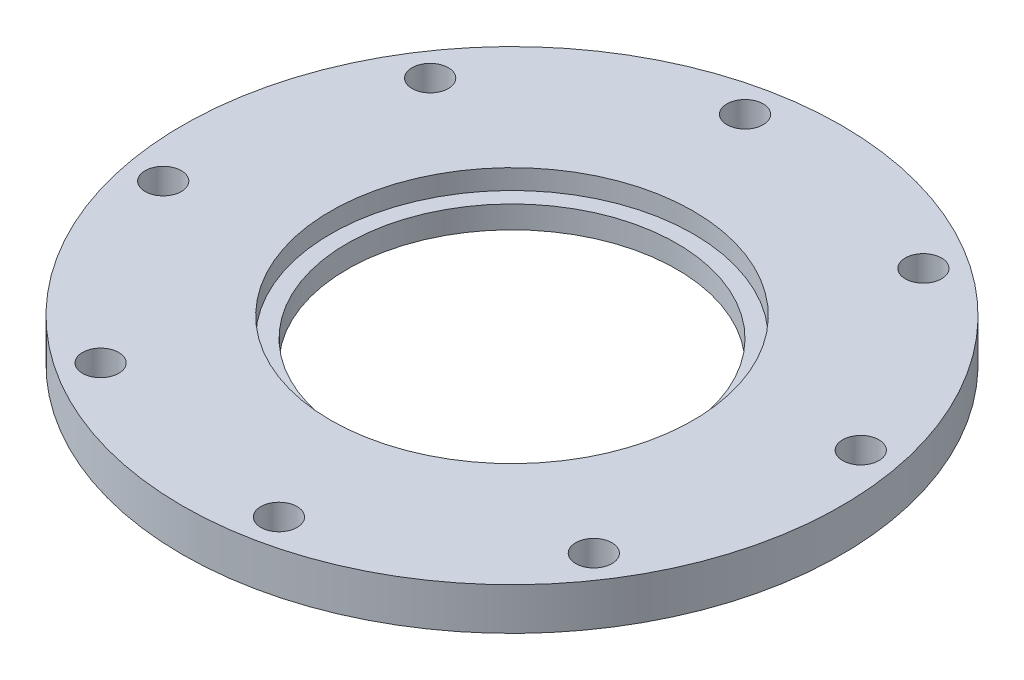
SolidWorks part; units mm, degrees
ref_plane "Front Plane" through (0, 0, 0) normal (0, 0, 1) x (1, 0, 0)
ref_plane "Top Plane" through (0, 0, 0) normal (0, 1, 0) x (1, 0, 0)
ref_plane "Right Plane" through (0, 0, 0) normal (1, 0, 0) x (0, 0, -1)
sketch "Sketch1" plane through (0, 0, 0) normal (0, 1, 0) x (1, 0, 0)
  circle A0 centre (0, 0) radius 50
  circle A1 centre (0, 0) radius 25
  circle A2 centre (0, 0) radius 35
  circle A3 centre (0, 35) radius 2.5
  circle A4 centre (0, 35) radius 2.9
  circle A5 centre (13.3939, 32.3358) radius 2.9
  circle A6 centre (24.7487, 24.7487) radius 2.9
  circle A7 centre (32.3358, 13.3939) radius 2.9
  circle A8 centre (35, 0) radius 2.9
  circle A9 centre (32.3358, -13.3939) radius 2.9
  circle A10 centre (24.7487, -24.7487) radius 2.9
  circle A11 centre (13.3939, -32.3358) radius 2.9
  circle A12 centre (0, -35) radius 2.9
  circle A13 centre (-13.3939, -32.3358) radius 2.9
  circle A14 centre (-24.7487, -24.7487) radius 2.9
  circle A15 centre (-32.3358, -13.3939) radius 2.9
  circle A16 centre (-35, 0) radius 2.9
  circle A17 centre (-32.3358, 13.3939) radius 2.9
  circle A18 centre (-24.7487, 24.7487) radius 2.9
  circle A19 centre (-13.3939, 32.3358) radius 2.9
  point P18 (0, 0)
  dimension "D1" = 100
  dimension "D2" = 50
  dimension "D3" = 70
  dimension "D4" = 5
  dimension "D5" = 0.4
  dimension "D6" = 16
extrude "Boss-Extrude1" add sketch "Sketch1" along normal blind 3.4 contours A0 A19 A2 A4 A5 A6 A7 A8 A9 A10 A11 A12 A13 A14 A15 A16 A17 A18 | A19 A2 A18 A17 A16 A15 A14 A13 A12 A11 A10 A9 A8 A7 A6 A5 A4 A1
sketch "Sketch2" plane through (0, 3.4, 0) normal (0, 1, 0) x (1, 0, 0)
  circle A0 centre (0, 0) radius 27.5
  circle A1 centre (0, 0) radius 50 construction
  circle A2 centre (0, 0) radius 50
  dimension "D1" = 55
extrude "Boss-Extrude2" add sketch "Sketch2" along normal blind 3
sketch "Sketch3" plane through (0, 0, 0) normal (0, -1, 0) x (1, 0, 0)
  line L0 (24.7487, 24.7487) -> (32.3358, 13.3939)
  line L1 (0, 0) -> (28.5423, 19.0713)
  line L2 (28.5423, 19.0713) -> (41.5735, 27.7785)
  circle A0 centre (0, 0) radius 35
  circle A1 centre (0, 35) radius 2.9
  circle A2 centre (13.3939, 32.3358) radius 2.9
  circle A3 centre (24.7487, 24.7487) radius 2.9
  circle A4 centre (32.3358, 13.3939) radius 2.9
  circle A5 centre (35, 0) radius 2.9
  circle A6 centre (32.3358, -13.3939) radius 2.9
  circle A7 centre (24.7487, -24.7487) radius 2.9
  circle A8 centre (13.3939, -32.3358) radius 2.9
  circle A9 centre (0, -35) radius 2.9
  circle A10 centre (-13.3939, -32.3358) radius 2.9
  circle A11 centre (-24.7487, -24.7487) radius 2.9
  circle A12 centre (-32.3358, -13.3939) radius 2.9
  circle A13 centre (-35, 0) radius 2.9
  circle A14 centre (-32.3358, 13.3939) radius 2.9
  circle A15 centre (-24.7487, 24.7487) radius 2.9
  circle A16 centre (-13.3939, 32.3358) radius 2.9
  circle A17 centre (-37.4161, -25.0007) radius 2
  circle A18 centre (0, 0) radius 45
  circle A19 centre (0, 0) radius 50 construction
  circle A20 centre (37.4161, 25.0007) radius 2
  circle A21 centre (44.1353, -8.7791) radius 2
  circle A22 centre (25.0007, -37.4161) radius 2
  circle A23 centre (-8.7791, -44.1353) radius 2
  circle A24 centre (-44.1353, 8.7791) radius 2
  circle A25 centre (-25.0007, 37.4161) radius 2
  circle A26 centre (8.7791, 44.1353) radius 2
  point P15 (0, 0)
  point P39 (37.4161, 25.0007)
  point P54 (0, 0)
  dimension "D1" = 70
  dimension "D3" = 90
  dimension "D4" = 4
  dimension "D2" = 16
  dimension "D5" = 8
extrude "Cut-Extrude1" cut sketch "Sketch3" against normal blind 6.4 contours A18 A23 | A18 A22 | A18 A22 | A18 A17 | A17 A18 | A18 A24 | A18 A24 | A18 A25 | A18 A25 | A18 A26 | A18 A26 | A18 A20 L2 | L2 A20 A18 | A18 A20 L2 | L2 A20 A18 | A18 A21 | A18 A21
sketch "Sketch4" plane through (0, 6.4, 0) normal (0, 1, 0) x (1, 0, 0)
  circle A0 centre (-8.7791, 44.1353) radius 2.75
  circle A1 centre (25.0007, 37.4161) radius 2.75
  circle A2 centre (44.1353, 8.7791) radius 2.75
  circle A3 centre (37.4161, -25.0007) radius 2.75
  circle A4 centre (8.7791, -44.1353) radius 2.75
  circle A5 centre (-25.0007, -37.4161) radius 2.75
  circle A6 centre (-44.1353, -8.7791) radius 2.75
  circle A7 centre (-37.4161, 25.0007) radius 2.75
  point P12 (0, 0)
  dimension "D2" = 8
extrude "Cut-Extrude2" cut sketch "Sketch4" against normal blind 5
equation "\"OD\"=100"
equation "\"ID1\"= 50"
equation "\"D2@Sketch1\"=\"ID1\""
equation "\"R_SUN\"=70"
equation "\"D3@Sketch1\"=\"R_SUN\""
equation "\"ROLL_TOL\"=0.4"
equation "\"D5@Sketch1\"=\"ROLL_TOL\""
equation "\"THICK_IN\"=3"
equation "\"D1@Boss-Extrude1\"=\"THICK_IN\"+\"ROLL_TOL\""
equation "\"D_OUT_BEAR\"=55"
equation "\"D1@Sketch2\"=\"D_OUT_BEAR\""
equation "\"THICK_OUT\"=3"
equation "\"D1@Boss-Extrude2\"=\"THICK_OUT\""
equation "\"D_SCREW\"=90"
equation "\"D3@Sketch3\"=\"D_SCREW\""
equation "\"SCREW_D\"=4"
equation "\"D4@Sketch3\"=\"SCREW_D\""
equation "\"D1@Cut-Extrude1\"=\"THICK_IN\"+\"THICK_OUT\"+\"ROLL_TOL\""
equation "\"INSERT_DIAM\"=5.5"
equation "\"D1@Sketch4\"=\"INSERT_DIAM\""
equation "\"D2@Sketch4\"=8"
equation "\"INSERT_THICK\"=5"
equation "\"D1@Cut-Extrude2\"=\"INSERT_THICK\""
